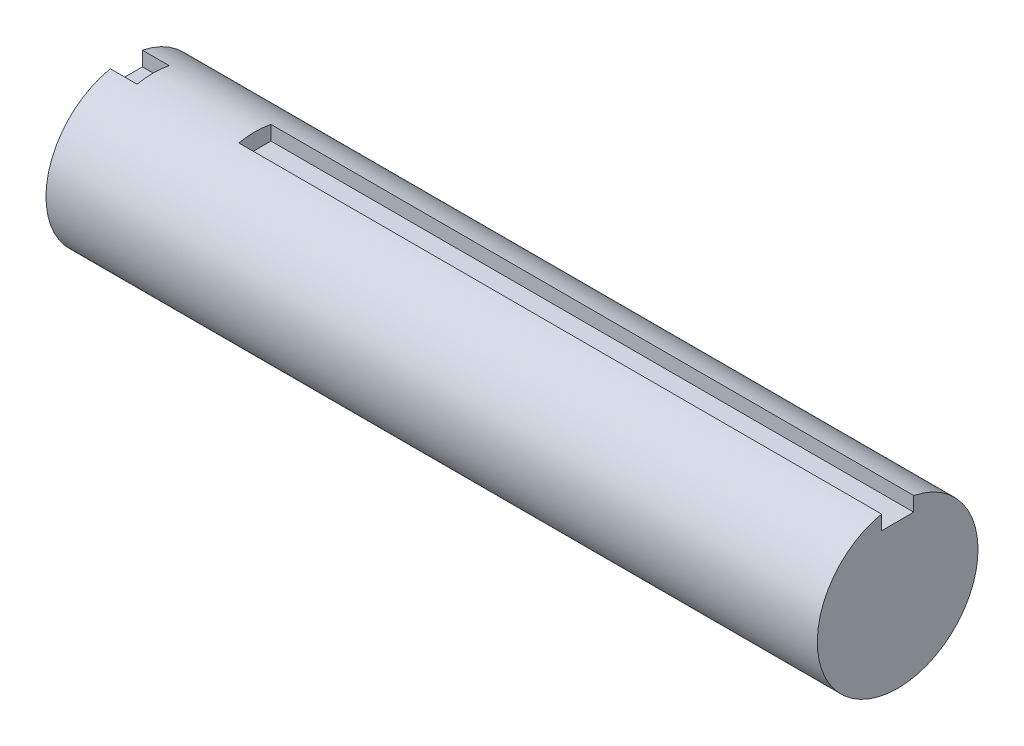
SolidWorks part; units mm, degrees
ref_plane "Front Plane" through (0, 0, 0) normal (0, 0, 1) x (1, 0, 0)
ref_plane "Top Plane" through (0, 0, 0) normal (0, 1, 0) x (1, 0, 0)
ref_plane "Right Plane" through (0, 0, 0) normal (1, 0, 0) x (0, 0, -1)
sketch "Sketch1" plane through (0, 0, 0) normal (1, 0, 0) x (0, 0, -1)
  circle A0 centre (0, 0) radius 38.1
  dimension "D1" = 76.2
extrude "Boss-Extrude1" add sketch "Sketch1" along normal blind 365.76
sketch "Sketch2" plane through (365.76, 0, 0) normal (1, 0, 0) x (0, 0, -1)
  line L0 (0, 0) -> (0, 38.1) construction
  line L2 (-7.62, 45.72) -> (7.62, 45.72)
  line L3 (-7.62, 45.72) -> (-7.62, 30.48)
  line L4 (-7.62, 30.48) -> (7.62, 30.48)
  line L5 (7.62, 45.72) -> (7.62, 30.48)
  circle A0 centre (0, 0) radius 38.1 construction
  dimension "D1" = 7.62
  dimension "D2" = 7.62
  dimension "D3" = 15.24
  dimension "D4" = 15.24
extrude "Cut-Extrude1" cut sketch "Sketch2" against normal blind 304.8
sketch "Sketch3" plane through (0, 0, 0) normal (-1, 0, 0) x (0, 0, 1)
  line L0 (0, 0) -> (0, 38.1) construction
  line L2 (-7.62, 45.72) -> (7.62, 45.72)
  line L3 (-7.62, 45.72) -> (-7.62, 30.48)
  line L4 (-7.62, 30.48) -> (7.62, 30.48)
  line L5 (7.62, 45.72) -> (7.62, 30.48)
  circle A0 centre (0, 0) radius 38.1 construction
  point P10 (0, 0)
  dimension "D1" = 7.62
  dimension "D2" = 15.24
  dimension "D3" = 15.24
  dimension "D4" = 7.62
extrude "Cut-Extrude2" cut sketch "Sketch3" against normal blind 12.7
